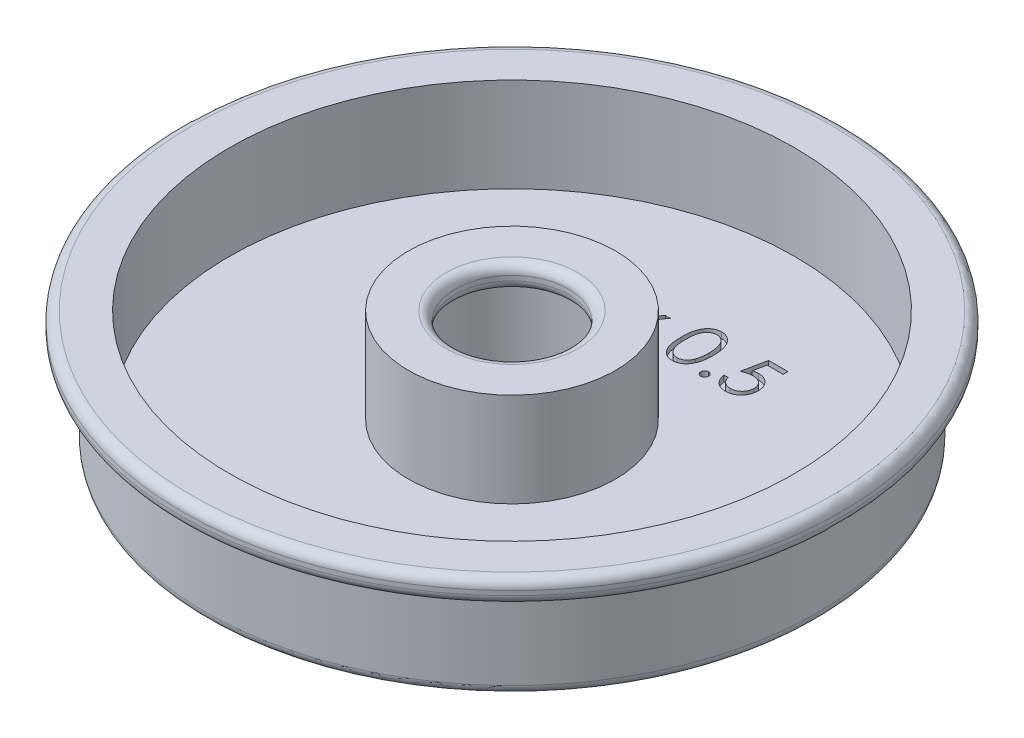
SolidWorks part; units mm, degrees
ref_plane "Front Plane" through (0, 0, 0) normal (0, 0, 1) x (1, 0, 0)
ref_plane "Top Plane" through (0, 0, 0) normal (0, 1, 0) x (1, 0, 0)
ref_plane "Right Plane" through (0, 0, 0) normal (1, 0, 0) x (0, 0, -1)
sketch "Sketch1" plane through (0, 0, 0) normal (0, 0, 1) x (1, 0, 0)
  line L0 (0, 0) -> (0, 11.1543)
  line L3 (13.97, 15.9118) -> (13.97, 3.2118)
  line L4 (13.97, 3.2118) -> (38.1, 3.2118)
  line L5 (38.1, 3.2118) -> (38.1, 15.9118)
  line L8 (40.005, 0.0368) -> (12.065, 0.0368)
  line L9 (41.275, 1.3068) -> (41.275, 11.5037)
  line L10 (42.545, 12.7737) -> (43.18, 12.7737)
  line L11 (44.45, 14.0437) -> (44.45, 14.6418)
  line L12 (38.1, 15.9118) -> (43.18, 15.9118)
  line L13 (13.97, 15.9118) -> (8.89, 15.9118)
  line L14 (7.62, 14.6418) -> (7.62, 14.0068)
  line L15 (10.795, 1.3068) -> (10.795, 11.4668)
  line L16 (9.525, 12.7368) -> (8.89, 12.7368)
  arc A0 (43.18, 15.9118) -> (44.45, 14.6418) centre (43.18, 14.6418) cw
  arc A1 (44.45, 14.0437) -> (43.18, 12.7737) centre (43.18, 14.0437) cw
  arc A2 (42.545, 12.7737) -> (41.275, 11.5037) centre (42.545, 11.5037) ccw
  arc A3 (41.275, 1.3068) -> (40.005, 0.0368) centre (40.005, 1.3068) cw
  arc A4 (12.065, 0.0368) -> (10.795, 1.3068) centre (12.065, 1.3068) cw
  arc A5 (10.795, 11.4668) -> (9.525, 12.7368) centre (9.525, 11.4668) ccw
  arc A6 (8.89, 12.7368) -> (7.62, 14.0068) centre (8.89, 14.0068) cw
  arc A7 (7.62, 14.6418) -> (8.89, 15.9118) centre (8.89, 14.6418) cw
  dimension "D10" = 1.27
  dimension "D1" = 3.175
  dimension "D2" = 6.35
  dimension "D3" = 3.175
  dimension "D4" = 6.35
  dimension "D5" = 3.175
  dimension "D6" = 13.97
  dimension "D7" = 38.1
  dimension "D8" = 3.1382
  dimension "D9" = 3.175
  dimension "D11" = 12.7
  dimension "D12" = 12.7
revolve "Revolve2" add sketch "Sketch1" angle 360 about L0
sketch "Sketch2" plane through (0, 3.2118, 0) normal (0, 1, 0) x (1, 0, 0)
  text T0 "3 x 0.5" font "Century Gothic" height in points 24
extrude "Cut-Extrude1" cut sketch "Sketch2" against normal blind 0.7937
